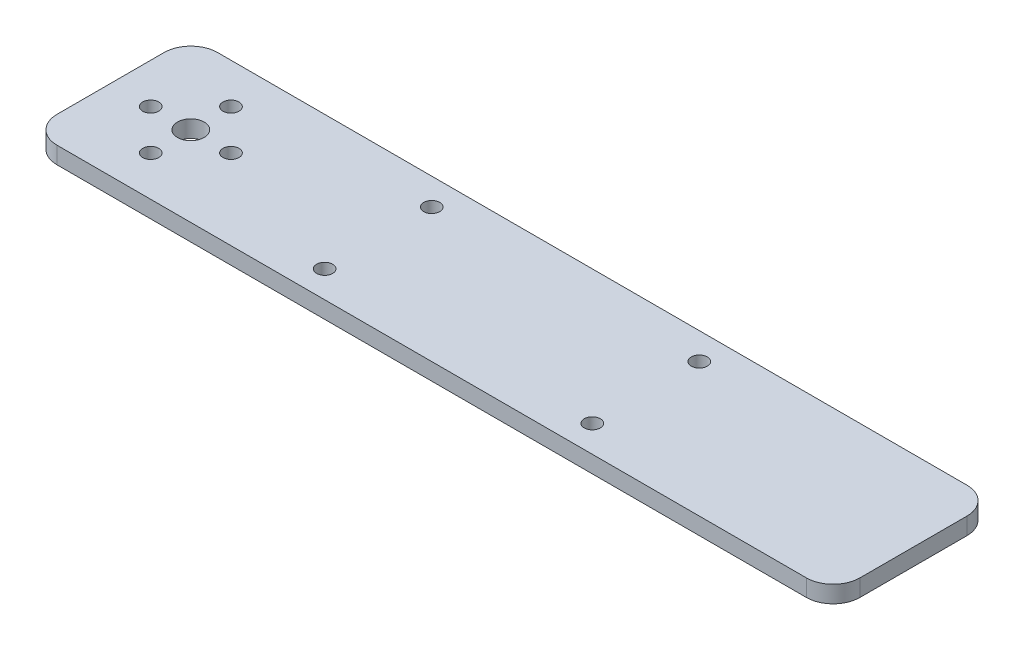
SolidWorks part; units mm, degrees
ref_plane "Front Plane" through (0, 0, 0) normal (0, 0, 1) x (1, 0, 0)
ref_plane "Top Plane" through (0, 0, 0) normal (0, 1, 0) x (1, 0, 0)
ref_plane "Right Plane" through (0, 0, 0) normal (1, 0, 0) x (0, 0, -1)
sketch "Sketch1" plane through (0, 0, 0) normal (0, 1, 0) x (1, 0, 0)
  line L1 (-15, 15) -> (135, 15)
  line L2 (-15, 15) -> (-15, -15)
  line L3 (-15, -15) -> (135, -15)
  line L4 (135, 15) -> (135, -15)
  point P4 (-15, 0)
  dimension "D1" = 150
  dimension "D2" = 30
  dimension "D3" = 15
extrude "Boss-Extrude1" add sketch "Sketch1" along normal blind 3.175
fillet "Fillet1" radius 5 4 edges at (135, 1.5875, 15) (135, 1.5875, -15) (-15, 1.5875, -15) (-15, 1.5875, 15)
sketch "Sketch2" plane through (0, 3.175, 0) normal (0, 1, 0) x (1, 0, 0)
  circle A6 centre (0, 0) radius 2.5
  dimension "D6" = 5
extrude "Cut-Extrude1" cut sketch "Sketch2" against normal through all
sketch "Sketch3" plane through (0, 3.175, 0) normal (0, 1, 0) x (1, 0, 0)
  line L0 (-15, 10) -> (-15, -10) construction
  circle A4 centre (7.5, 0) radius 1.5
  circle A5 centre (0, 0) radius 2.5 construction
  circle A6 centre (0, -7.5) radius 1.5
  circle A7 centre (-7.5, 0) radius 1.5
  circle A8 centre (0, 7.5) radius 1.5
  point P4 (0, 0)
  point P7 (-15, 0)
  dimension "D1" = 7.5
  dimension "D2" = 3
  dimension "D3" = 15
extrude "Cut-Extrude3" cut sketch "Sketch3" against normal through all
sketch "Sketch4" plane through (0, 3.175, 0) normal (0, 1, 0) x (1, 0, 0)
  line L0 (-15, 0) -> (135, 0) construction
  line L1 (-15, 10) -> (-15, -10) construction
  line L2 (135, -10) -> (135, 10) construction
  line L3 (60, 15) -> (60, -15) construction
  line L4 (130, 15) -> (-10, 15) construction
  line L5 (-10, -15) -> (130, -15) construction
  circle A0 centre (35, -10) radius 1.5
  circle A1 centre (85, -10) radius 1.5
  circle A2 centre (85, 10) radius 1.5
  circle A3 centre (35, 10) radius 1.5
  dimension "D3" = 3
  dimension "D1" = 25
  dimension "D2" = 5
extrude "Cut-Extrude4" cut sketch "Sketch4" against normal blind 10
